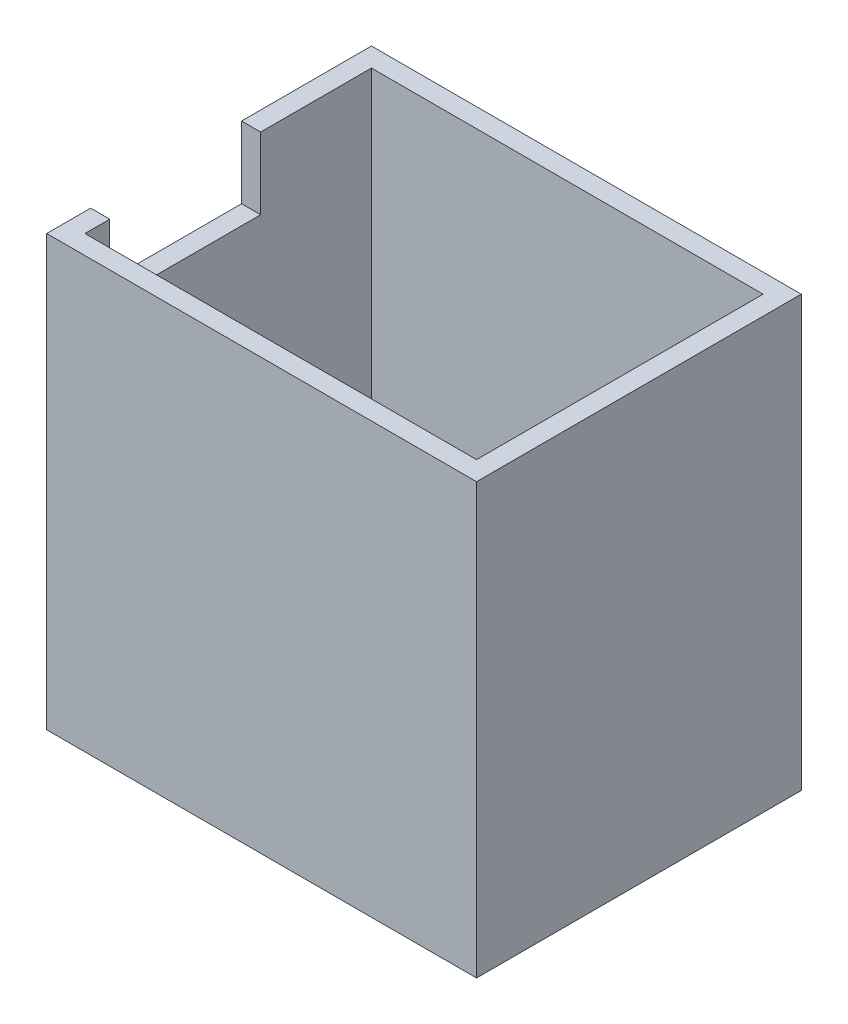
SolidWorks part; units mm, degrees
ref_plane "Front Plane" through (0, 0, 0) normal (0, 0, 1) x (1, 0, 0)
ref_plane "Top Plane" through (0, 0, 0) normal (0, 1, 0) x (1, 0, 0)
ref_plane "Right Plane" through (0, 0, 0) normal (1, 0, 0) x (0, 0, -1)
sketch "Sketch1" plane through (0, 0, 0) normal (0, 1, 0) x (1, 0, 0)
  line L1 (-28.575, -21.59) -> (28.575, -21.59)
  line L2 (-28.575, -21.59) -> (-28.575, 21.59)
  line L3 (-28.575, 21.59) -> (28.575, 21.59)
  line L4 (28.575, -21.59) -> (28.575, 21.59)
  line L5 (-28.575, -21.59) -> (28.575, 21.59) construction
  line L6 (-28.575, 21.59) -> (28.575, -21.59) construction
  point P0 (0, 0)
  dimension "D1" = 57.15
  dimension "D2" = 43.18
extrude "Base" add sketch "Sketch1" along normal blind 57.15
sketch "Sketch2" plane through (0, 57.15, 0) normal (0, 1, 0) x (1, 0, 0)
  line L1 (26.035, -19.05) -> (-26.035, -19.05)
  line L2 (26.035, -19.05) -> (26.035, 19.05)
  line L3 (26.035, 19.05) -> (-26.035, 19.05)
  line L4 (-26.035, -19.05) -> (-26.035, 19.05)
  line L5 (26.035, -19.05) -> (-26.035, 19.05) construction
  line L6 (26.035, 19.05) -> (-26.035, -19.05) construction
  point P0 (0, 0)
  dimension "D1" = 38.1
  dimension "D2" = 52.07
extrude "Pocket" cut sketch "Sketch2" against normal blind 47.9552
sketch "Sketch3" plane through (0, 0, 0) normal (0, -1, 0) x (-1, 0, 0)
  line L0 (28.575, 0) -> (-28.575, 0) construction
  line L1 (7.493, -7.747) -> (-10.795, -7.747)
  line L2 (7.493, -7.747) -> (7.493, 7.747)
  line L3 (7.493, 7.747) -> (-10.795, 7.747)
  line L4 (-10.795, -7.747) -> (-10.795, 7.747)
  line L5 (7.493, -7.747) -> (-10.795, 7.747) construction
  line L6 (7.493, 7.747) -> (-10.795, -7.747) construction
  line L7 (28.575, 21.59) -> (28.575, -21.59) construction
  line L8 (-28.575, -21.59) -> (-28.575, 21.59) construction
  point P0 (-1.651, 0)
  dimension "D1" = 15.494
  dimension "D2" = 18.288
  dimension "D3" = 21.082
extrude "LinActHole" cut sketch "Sketch3" against normal through all
sketch "Sketch4" plane through (-28.575, 0, 0) normal (-1, 0, 0) x (0, 0, 1)
  line L0 (-21.59, 57.15) -> (21.59, 57.15) construction
  line L1 (15.748, 57.15) -> (-4.318, 57.15)
  line L2 (15.748, 57.15) -> (15.748, 47.625)
  line L3 (15.748, 47.625) -> (-4.318, 47.625)
  line L4 (-4.318, 57.15) -> (-4.318, 47.625)
  line L5 (21.59, 57.15) -> (21.59, 0) construction
  line L6 (-21.59, 57.15) -> (-21.59, 0) construction
  dimension "D1" = 5.842
  dimension "D2" = 17.272
  dimension "D3" = 9.525
extrude "RollMotorHole" cut sketch "Sketch4" against normal up to next
sketch "Sketch5" plane through (0, 0, 0) normal (0, -1, 0) x (1, 0, 0)
  line L1 (17.6249, -13.716) -> (24.2289, -13.716)
  line L2 (15.0849, -11.176) -> (15.0849, 11.176)
  line L3 (17.6249, 13.716) -> (24.2289, 13.716)
  line L4 (24.2289, -13.716) -> (24.2289, 13.716)
  line L5 (15.0849, -13.716) -> (24.2289, 13.716) construction
  line L6 (15.0849, 13.716) -> (24.2289, -13.716) construction
  arc A0 (15.0849, -11.176) -> (17.6249, -13.716) centre (17.6249, -11.176) ccw
  arc A1 (15.0849, 11.176) -> (17.6249, 13.716) centre (17.6249, 11.176) cw
  point P0 (19.6569, 0)
  dimension "D3" = 2.54
  dimension "D1" = 27.432
  dimension "D2" = 9.144
extrude "DviHole" cut sketch "Sketch5" against normal up to next
hole_wizard "CBORE for #4 Socket Head Cap Screw1" positions "Sketch7" profile "Sketch6" counterbore size "#4" standard "ANSI Inch" end condition through all
sketch "Sketch7" plane through (0, 0, 0) normal (0, -1, 0) x (-1, 0, 0)
  line L0 (-19.6569, 21.59) -> (-19.6569, -21.59) construction
  line L1 (-28.575, 21.59) -> (28.575, 21.59) construction
  line L2 (28.575, -21.59) -> (-28.575, -21.59) construction
  line L3 (-24.2289, 13.716) -> (-24.2289, -13.716) construction
  line L4 (-24.2289, 0) -> (-15.0849, 0) construction
  line L5 (-15.0849, -11.176) -> (-15.0849, 11.176) construction
  point P0 (-19.6569, 16.256)
  point P2 (-19.6569, -16.256)
  dimension "D1" = 4.572
  dimension "D2" = 32.512
sketch "Sketch6" plane through (19.6569, 0, -16.256) normal (1, 0, 0) x (0, 0, -1)
  line L0 (0, 0) -> (0, 57.15)
  line L1 (0, 57.15) -> (1.6319, 57.15)
  line L3 (1.6319, 57.15) -> (1.632, 2.8448)
  line L4 (1.632, 2.8448) -> (2.7788, 2.8448)
  line L5 (2.7788, 2.8448) -> (2.7788, 0)
  line L7 (2.7788, 0) -> (0, 0)
  line L11 (0, -6.35) -> (0, 107.95) construction
  dimension "Thru Hole Dia." = 3.2639
  dimension "Thru Hole Depth" = 57.15
  dimension "C'Bore Dia." = 5.5575
  dimension "C'Bore Depth" = 2.8448
hole_wizard "CBORE for #8 Socket Head Cap Screw1" positions "Sketch9" profile "Sketch8" counterbore size "#8" standard "ANSI Inch" end condition through all
sketch "Sketch9" plane through (0, 0, 0) normal (0, -1, 0) x (-1, 0, 0)
  line L0 (3.175, -21.59) -> (3.175, 21.59) construction
  line L1 (28.575, -21.59) -> (-28.575, -21.59) construction
  line L2 (-28.575, 21.59) -> (28.575, 21.59) construction
  line L3 (28.575, 0) -> (-28.575, 0) construction
  line L4 (28.575, 21.59) -> (28.575, -21.59) construction
  line L5 (-28.575, -21.59) -> (-28.575, 21.59) construction
  point P0 (3.175, 14.605)
  point P2 (3.175, -14.605)
  dimension "D1" = 31.75
  dimension "D2" = 29.21
sketch "Sketch8" plane through (-3.175, 0, -14.605) normal (1, 0, 0) x (0, 0, -1)
  line L0 (0, 0) -> (0, 57.15)
  line L1 (0, 57.15) -> (2.2479, 57.15)
  line L3 (2.2479, 57.15) -> (2.2479, 4.1656)
  line L4 (2.2479, 4.1656) -> (3.9688, 4.1656)
  line L5 (3.9688, 4.1656) -> (3.9688, 0)
  line L7 (3.9688, 0) -> (0, 0)
  line L11 (0, -6.35) -> (0, 107.95) construction
  dimension "Thru Hole Dia." = 4.4958
  dimension "Thru Hole Depth" = 57.15
  dimension "C'Bore Dia." = 7.9375
  dimension "C'Bore Depth" = 4.1656
fillet "Fillet1" radius 0.254 4 edges at (20.7838, 1.4224, -13.716) (18.53, 1.4224, -13.716) (18.53, 1.4224, 13.716) (20.7838, 1.4224, 13.716)
